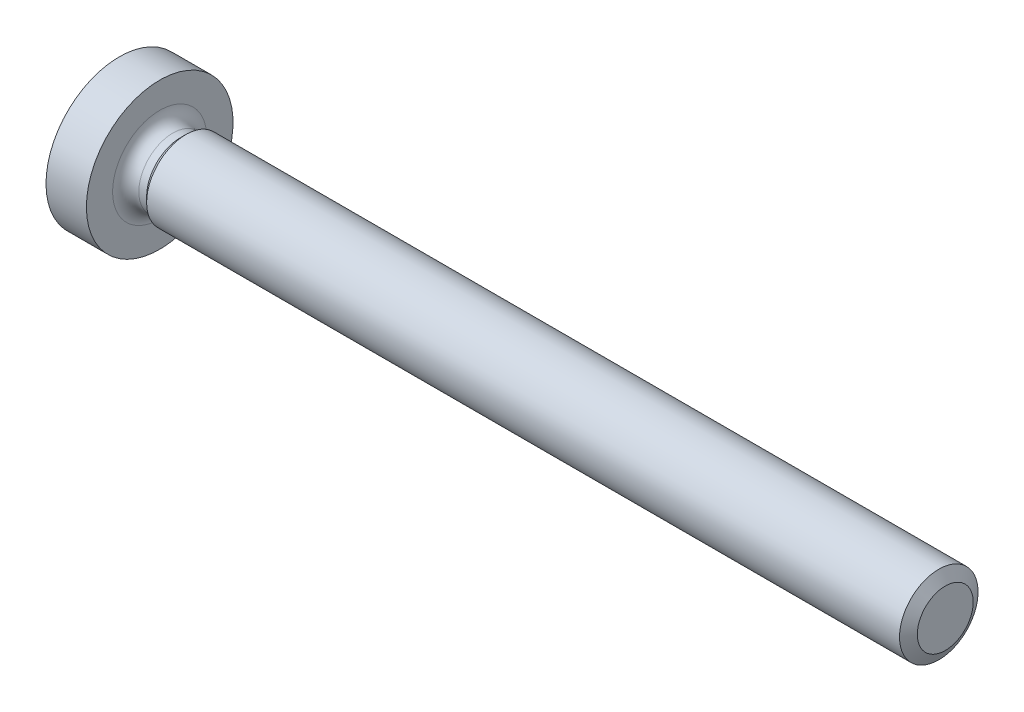
SolidWorks part; units mm, degrees
revolve "基体-旋转" add sketch "草图2" angle 360 about L0
sketch "草图2" plane through (0, 0, 0) normal (0, 0, 1) x (1, 0, 0)
  line L0 (-1.3318, 0) -> (6.5885, 0) construction
  line L1 (0, 0) -> (32.4, 0)
  line L2 (32.4, 0) -> (32.4, 1.5)
  line L3 (32.4, 1.5) -> (3.4, 1.5)
  line L4 (3.4, 1.5) -> (3.199, 1.299)
  line L5 (3.199, 1.299) -> (2.901, 1.299)
  line L6 (2.4, 1.8) -> (2.4, 2.8)
  line L7 (2.4, 2.8) -> (0.8575, 2.8)
  arc A0 (2.4, 1.8) -> (2.901, 1.299) centre (2.901, 1.8) ccw
  arc A1 (0, 0) -> (0.8575, 2.8) centre (5, 0) cw
  dimension "D3" = 5
  dimension "dk" = 5.6
  dimension "d" = 3
  dimension "l" = 30
  dimension "a" = 1
  dimension "D1" = 45
  dimension "D2" = 2.598
  dimension "da" = 3.6
  dimension "k" = 2.4
cosmetic thread "装饰螺纹线1" parameters "D1"=29, "D2"=2.598
ref_plane "前视" through (0, 0, 0) normal (0, 0, 1) x (1, 0, 0)
ref_plane "上视" through (0, 0, 0) normal (0, 1, 0) x (1, 0, 0)
ref_plane "右视" through (0, 0, 0) normal (1, 0, 0) x (0, 0, -1)
sketch "尺寸草图" plane through (0, 0, 0) normal (0, 0, 1) x (1, 0, 0)
  line L0 (0, 0) -> (30, 0)
  line L1 (0, 0) -> (0, 5.6)
  line L2 (30, 0) -> (30, 3.6)
  point P5 (0, 3)
  point P6 (29.5, 0)
  point P7 (1, 0)
  point P8 (2.4, 0)
  point P9 (25, 0)
  point P10 (3, 0)
  point P11 (28.2, 0)
  dimension "dk" = 5.6
  dimension "d" = 3
  dimension "l" = 30
  dimension "a" = 1
  dimension "da" = 3.6
  dimension "k" = 2.4
  dimension "P" = 0.5
  dimension "rf" = 5
  dimension "m" = 3
  dimension "h" = 1.8
sketch "草图3" plane through (0, 0, 0) normal (0, 0, 1) x (1, 0, 0)
  line L0 (32.1527, 1.5) -> (32.6527, 1.5)
  line L1 (32.6527, 1.5) -> (32.4, 1.067)
  line L2 (32.4, 1.067) -> (32.1527, 1.5)
  line L3 (32.4, 1.5) -> (3.4, 1.5) construction
  line L4 (32.4, -1.5) -> (32.4, 1.5) construction
  line L5 (-0.2428, 0) -> (7.1644, 0) construction
  line L6 (-1.3318, 0) -> (6.5885, 0) construction
  dimension "P" = 0.5
  dimension "D1" = 0.433
  dimension "D2" = 60
revolve "切除-旋转1" cut sketch "草图3" angle 360 about L5
sketch "草图5" plane through (0, 0, 0) normal (1, 0, 0) x (0, 0, -1)
  line L1 (0.25, 1.5) -> (-0.25, 1.5)
  line L2 (0.25, 1.5) -> (0.25, -1.5)
  line L3 (0.25, -1.5) -> (-0.25, -1.5)
  line L4 (-0.25, 1.5) -> (-0.25, -1.5)
  point P4 (0.25, 0)
  point P5 (0, 1.5)
  dimension "m" = 3
  dimension "D1" = 0.5
ref_plane "基准面1" through (1.8, 0, 0) normal (1, 0, 0) x (0, 0, -1)
pattern_linear "阵列(线性)1" [suppressed] count 59 spacing 0.5 along (1, 0, 0)
sketch "草图6" plane through (1.8, 0, 0) normal (1, 0, 0) x (0, 0, -1)
  point P0 (0, 0)
loft "切除-放样1" cut profiles "草图6", "草图5"
ref_plane "基准面2" through (0, 0, 0) normal (0, -0.7071, 0.7071) x (1, 0, 0)
mirror "镜向1" about plane through (0, 0, 0) normal (0, -0.7071, 0.7071) of "切除-放样1"
equation "\"l@草图2\" = \"l@尺寸草图\""
equation "\"dk@草图2\" = \"dk@尺寸草图\""
equation "\"k@草图2\" = \"k@尺寸草图\""
equation "\"D2@草图2\" = \"d@尺寸草图\"*0.866"
equation "\"a@草图2\" = \"a@尺寸草图\""
equation "\"D3@草图2\" = \"rf@尺寸草图\""
equation "\"d@草图2\" = \"d@尺寸草图\""
equation "\"da@草图2\" = \"da@尺寸草图\""
equation "\"D2@装饰螺纹线1\" = \"d@尺寸草图\"*0.866"
equation "\"D1@装饰螺纹线1\" = \"l@尺寸草图\"-\"a@尺寸草图\""
equation "\"P@草图3\" = \"P@尺寸草图\""
equation "\"D1@草图3\" = \"P@尺寸草图\"*0.866"
equation "\"h@基准面1\" = \"h@尺寸草图\""
equation "\"D1@草图5\" = \"P@尺寸草图\""
equation "\"m@草图5\" = \"m@尺寸草图\""
equation "\"D3@阵列(线性)1\" = \"P@尺寸草图\""
equation "\"D1@阵列(线性)1\" = (\"l@尺寸草图\"-\"a@尺寸草图\")/\"P@尺寸草图\"+1"
